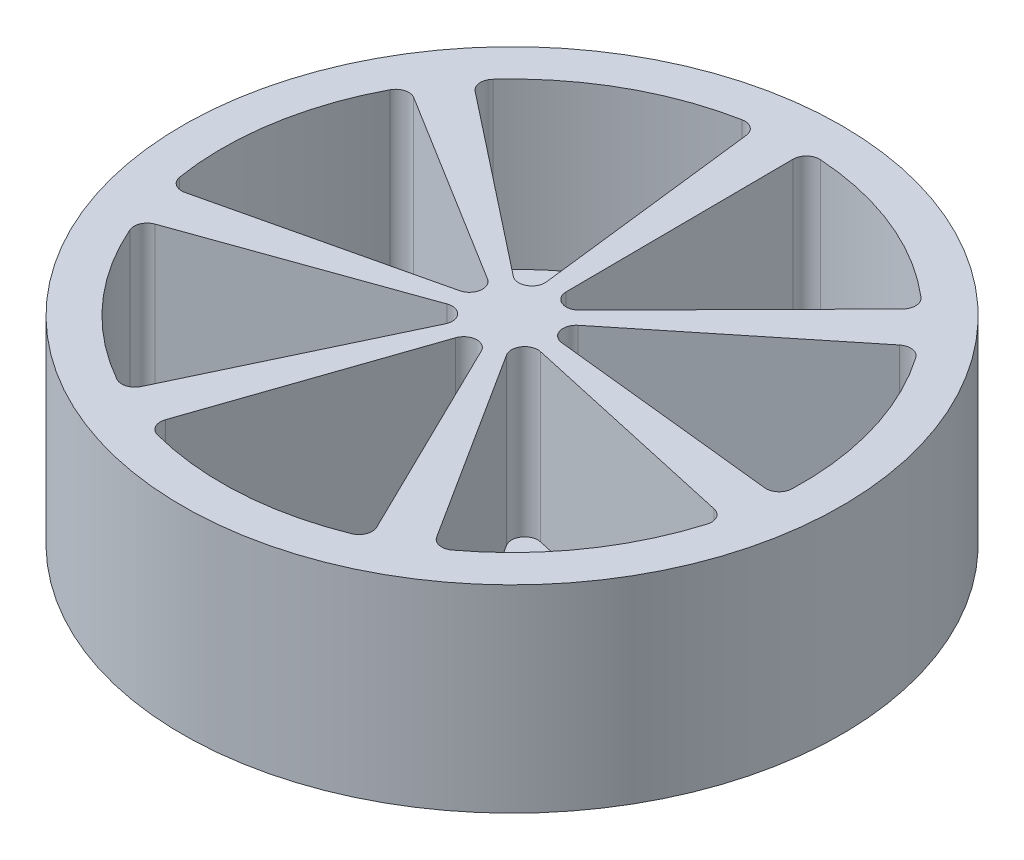
SolidWorks part; units mm, degrees
material "ABS"
ref_plane "Front Plane" through (0, 0, 0) normal (0, 0, 1) x (1, 0, 0)
ref_plane "Top Plane" through (0, 0, 0) normal (0, 1, 0) x (1, 0, 0)
ref_plane "Right Plane" through (0, 0, 0) normal (1, 0, 0) x (0, 0, -1)
sketch "Sketch1" plane through (0, 0, 0) normal (0, 1, 0) x (1, 0, 0)
  circle A0 centre (0, 0) radius 63.5
  dimension "D1" = 127
extrude "Boss-Extrude1" add sketch "Sketch1" along normal blind 38.1
sketch "Sketch2" plane through (0, 38.1, 0) normal (0, 1, 0) x (1, 0, 0)
  line L0 (-1.782, -9.1113) -> (-16.0573, -50.7387)
  line L1 (2.9021, -8.8187) -> (22.2474, -48.3457)
  line L2 (0.2069, -3.3118) -> (23.4176, -50.7365) construction
  line L3 (0, 0) -> (25.1229, -51.3319) construction
  line L4 (0, 0) -> (-18.5387, -54.0596) construction
  line L5 (0.2069, -3.3118) -> (-16.9208, -53.2566) construction
  line L6 (8.7042, -3.2294) -> (51.6692, -12.7493)
  line L9 (6.0125, -7.074) -> (29.6575, -44.1892)
  line L10 (7.9518, 4.7917) -> (42.183, 32.4476)
  line L11 (9.2794, 0.2902) -> (53.0397, -4.3643)
  line L12 (1.2116, 9.2045) -> (0.9321, 53.2107)
  line L13 (5.5587, 7.4359) -> (36.4818, 38.747)
  line L14 (-6.441, 6.6862) -> (-41.0207, 33.9051)
  line L15 (-2.3478, 8.9822) -> (-7.5476, 52.681)
  line L16 (-9.2434, -0.867) -> (-52.0841, -10.9317)
  line L17 (-8.4864, 3.7647) -> (-45.8935, 26.9451)
  line L18 (-5.0853, -7.7673) -> (-23.9271, -47.5368)
  line L19 (-8.2345, -4.2876) -> (-49.6807, -19.081)
  arc A0 (-18.5387, -54.0596) -> (25.1229, -51.3319) centre (0, 0) ccw construction
  circle A1 centre (0, 0) radius 63.5 construction
  arc A2 (-14.3049, -54.018) -> (20.9168, -51.8176) centre (0, 0) ccw
  arc A3 (-16.9208, -53.2566) -> (23.4176, -50.7365) centre (0, 0) ccw construction
  arc A4 (20.9168, -51.8176) -> (22.2474, -48.3457) centre (19.966, -49.4622) ccw
  arc A5 (-16.0573, -50.7387) -> (-14.3049, -54.018) centre (-13.6547, -51.5626) ccw
  arc A6 (-1.782, -9.1113) -> (2.9021, -8.8187) centre (0.6207, -9.9353) cw
  arc A7 (6.0125, -7.074) -> (8.7042, -3.2294) centre (8.1547, -5.7093) cw
  arc A8 (33.314, -44.8637) -> (53.554, -15.9543) centre (0, 0) ccw
  arc A9 (29.6575, -44.1892) -> (33.314, -44.8637) centre (31.7998, -42.8244) ccw
  arc A10 (53.554, -15.9543) -> (51.6692, -12.7493) centre (51.1198, -15.2291) ccw
  arc A11 (9.2794, 0.2902) -> (7.9518, 4.7917) centre (9.548, 2.8159) cw
  arc A12 (55.8468, -1.9261) -> (45.864, 31.9229) centre (0, 0) ccw
  arc A13 (53.0397, -4.3643) -> (55.8468, -1.9261) centre (53.3083, -1.8385) ccw
  arc A14 (45.864, 31.9229) -> (42.183, 32.4476) centre (43.7793, 30.4718) ccw
  arc A15 (5.5587, 7.4359) -> (1.2116, 9.2045) centre (3.7515, 9.2207) cw
  arc A16 (36.3258, 42.4619) -> (3.6374, 55.7615) centre (0, 0) ccw
  arc A17 (36.4818, 38.747) -> (36.3258, 42.4619) centre (34.6746, 40.5318) ccw
  arc A18 (3.6374, 55.7615) -> (0.9321, 53.2107) centre (3.4721, 53.2269) ccw
  arc A19 (-2.3478, 8.9822) -> (-6.441, 6.6862) centre (-4.87, 8.6821) cw
  arc A20 (-10.5493, 54.8752) -> (-41.3282, 37.6106) centre (0, 0) ccw
  arc A21 (-7.5476, 52.681) -> (-10.5493, 54.8752) centre (-10.0698, 52.3809) ccw
  arc A22 (-41.3282, 37.6106) -> (-41.0207, 33.9051) centre (-39.4496, 35.901) ccw
  arc A23 (-8.4864, 3.7647) -> (-9.2434, -0.867) centre (-9.8243, 1.6057) cw
  arc A24 (-49.4805, 25.9664) -> (-55.1728, -8.8619) centre (0, 0) ccw
  arc A25 (-45.8935, 26.9451) -> (-49.4805, 25.9664) centre (-47.2314, 24.7861) ccw
  arc A26 (-55.1728, -8.8619) -> (-52.0841, -10.9317) centre (-52.665, -8.4591) ccw
  arc A27 (-8.2345, -4.2876) -> (-5.0853, -7.7673) centre (-7.3807, -6.6798) cw
  arc A28 (-51.1519, -22.4957) -> (-27.4712, -48.6611) centre (0, 0) ccw
  arc A29 (-49.6807, -19.081) -> (-51.1519, -22.4957) centre (-48.8268, -21.4731) ccw
  arc A30 (-27.4712, -48.6611) -> (-23.9271, -47.5368) centre (-26.2225, -46.4493) ccw
  point P14 (0, 0)
  point P79 (0, 0)
  dimension "D1" = 6.35
  dimension "D3" = 2.54
  dimension "D2" = 1.27
  dimension "D4" = 7
extrude "Cut-Extrude2" cut sketch "Sketch2" against normal offset from surface (31.75 mm away) 6.35 up to face at (0, 0, 63.5)
